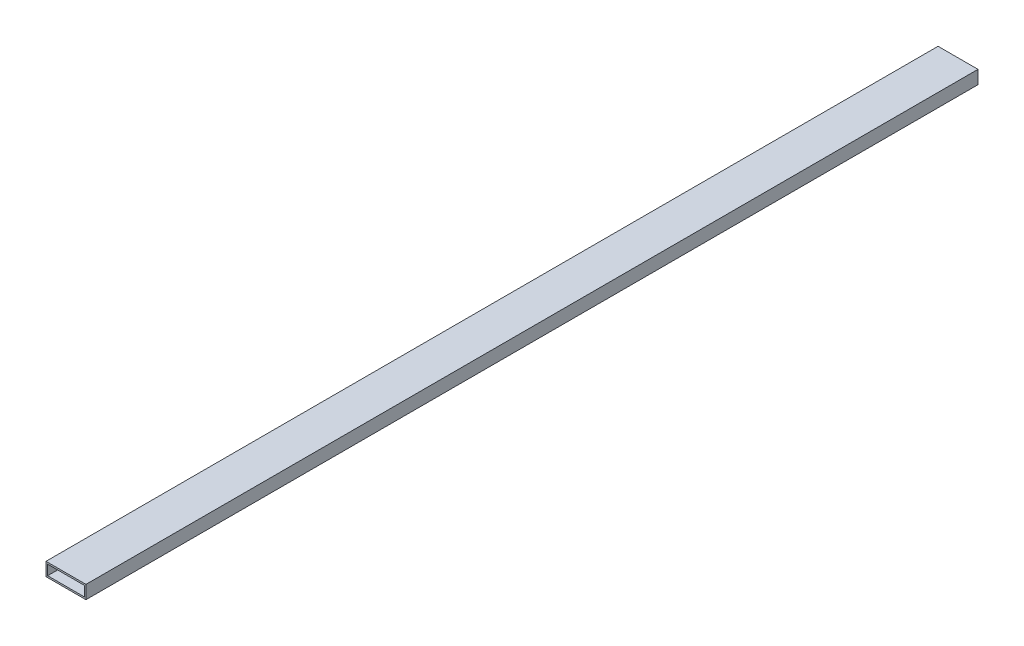
SolidWorks part; units mm, degrees
ref_plane "Front Plane" through (0, 0, 0) normal (0, 0, 1) x (1, 0, 0)
ref_plane "Top Plane" through (0, 0, 0) normal (0, 1, 0) x (1, 0, 0)
ref_plane "Right Plane" through (0, 0, 0) normal (1, 0, 0) x (0, 0, -1)
sketch "Sketch1" plane through (0, 0, 0) normal (0, 0, 1) x (1, 0, 0)
  line L1 (-38.1, 12.7) -> (38.1, 12.7)
  line L2 (-38.1, 12.7) -> (-38.1, -12.7)
  line L3 (-38.1, -12.7) -> (38.1, -12.7)
  line L4 (38.1, 12.7) -> (38.1, -12.7)
  line L5 (-38.1, 12.7) -> (38.1, -12.7) construction
  line L6 (-38.1, -12.7) -> (38.1, 12.7) construction
  point P0 (0, 0)
  dimension "D1" = 76.2
  dimension "D2" = 25.4
extrude "Extrude1" add sketch "Sketch1" against normal mid plane 1701.8
sketch "Sketch2" plane through (0, 0, 850.9) normal (0, 0, 1) x (1, 0, 0)
  line L8 (34.925, -9.525) -> (34.925, 9.525)
  line L9 (34.925, 9.525) -> (-34.925, 9.525)
  line L10 (-34.925, 9.525) -> (-34.925, -9.525)
  line L11 (-34.925, -9.525) -> (34.925, -9.525)
  line L12 (34.925, -9.525) -> (34.925, 9.525)
  line L13 (34.925, 9.525) -> (-34.925, 9.525)
  line L14 (-34.925, 9.525) -> (-34.925, -9.525)
  line L15 (-34.925, -9.525) -> (34.925, -9.525)
  dimension "D1" = 3.175
extrude "Extrude2" cut sketch "Sketch2" against normal through all
